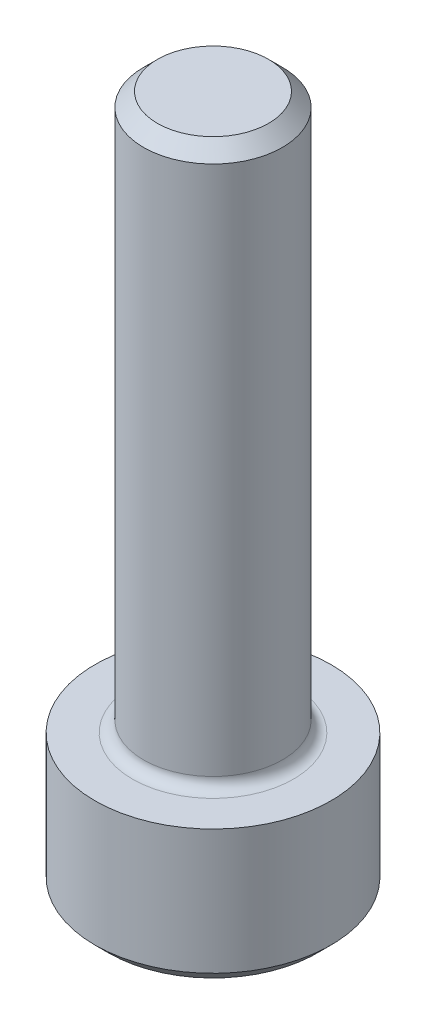
SolidWorks part; units mm, degrees
ref_plane "Front Plane" through (0, 0, 0) normal (0, 0, 1) x (1, 0, 0)
ref_plane "Top Plane" through (0, 0, 0) normal (0, 1, 0) x (1, 0, 0)
ref_plane "Right Plane" through (0, 0, 0) normal (1, 0, 0) x (0, 0, -1)
sketch "Sketch2" plane through (0, 0, 0) normal (0, 1, 0) x (1, 0, 0)
  circle A0 centre (0, 0) radius 2.5
extrude "Boss-Extrude1" add sketch "Sketch2" along normal blind 20
sketch "Sketch3" plane through (0, 0, 0) normal (0, 1, 0) x (1, 0, 0)
  circle A0 centre (0, 0) radius 4.25
extrude "Boss-Extrude2" add sketch "Sketch3" against normal blind 5
fillet "Fillet1" radius 0.4 1 edges at (0, 0, 2.5)
chamfer "Chamfer1" distance 0.5 angle 45 2 edges at (0, 20, 2.5) (0, -5, 4.25)
sketch "Sketch4" plane through (0, -5, 0) normal (0, -1, 0) x (1, 0, 0)
  line L1 (0, 2.3094) -> (-2, 1.1547)
  line L2 (-2, 1.1547) -> (-2, -1.1547)
  line L3 (-2, -1.1547) -> (0, -2.3094)
  line L4 (0, -2.3094) -> (2, -1.1547)
  line L5 (2, -1.1547) -> (2, 1.1547)
  line L6 (2, 1.1547) -> (0, 2.3094)
  circle A0 centre (0, 0) radius 2 construction
extrude "Cut-Extrude1" cut sketch "Sketch4" against normal blind 2.5
